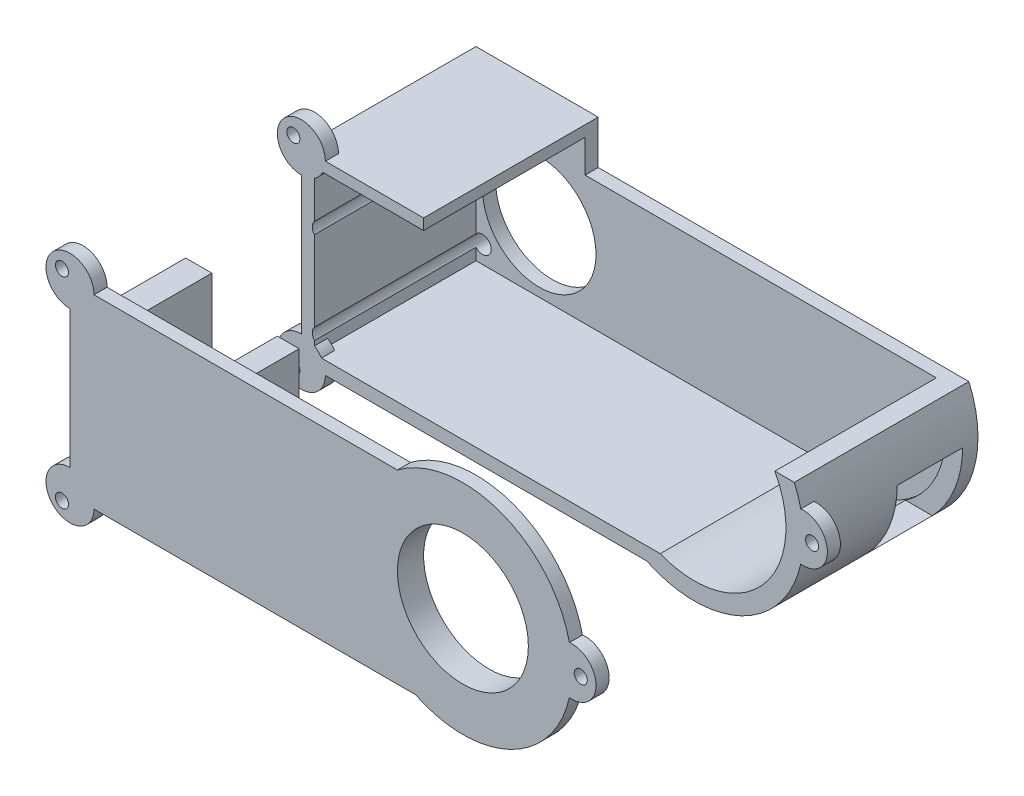
SolidWorks part; units mm, degrees
ref_plane "Front Plane" through (0, 0, 0) normal (0, 0, 1) x (1, 0, 0)
ref_plane "Top Plane" through (0, 0, 0) normal (0, 1, 0) x (1, 0, 0)
ref_plane "Right Plane" through (0, 0, 0) normal (1, 0, 0) x (0, 0, -1)
sketch "Sketch1" plane through (0, 0, 0) normal (0, 0, 1) x (1, 0, 0)
  line L1 (0, 0) -> (75, 0)
  line L2 (0, 0) -> (0, -42.5)
  line L3 (0, -42.5) -> (79.1028, -42.5)
  arc A0 (79.1028, -42.5) -> (75, 0) centre (90, -20) ccw
  dimension "D4" = 50
extrude "Boss-Extrude1" add sketch "Sketch1" along normal blind 40
sketch "Sketch2" plane through (0, 0, 40) normal (0, 0, 1) x (1, 0, 0)
  line L0 (0, 0) -> (0, -42.5) construction
  line L1 (3, -2.5) -> (78.3918, -2.5)
  line L2 (3, -2.5) -> (3, -39.5)
  line L3 (3, -39.5) -> (82.2058, -39.5)
  line L4 (75, 0) -> (0, 0) construction
  arc A0 (82.2058, -39.5) -> (78.3918, -2.5) centre (90, -20) ccw
  arc A1 (79.1028, -42.5) -> (75, 0) centre (90, -20) ccw construction
  dimension "D3" = 42
  dimension "D1" = 3
  dimension "D2" = 37
  dimension "D4" = 2.5
extrude "Cut-Extrude1" cut sketch "Sketch2" against normal blind 37
sketch "Sketch8" plane through (0, 0, 0) normal (0, 0, -1) x (-1, 0, 0)
  line L0 (-75, 0) -> (0, 0) construction
  line L1 (-66.3291, 0) -> (-28, 0)
  line L2 (-118, 0) -> (-118, -10)
  line L3 (-118, -10) -> (-28, -10)
  line L4 (-28, 0) -> (-28, -10)
  line L7 (-3, -2.5) -> (-3, -39.5) construction
  line L10 (-118, 0) -> (-118, 13.3555)
  line L11 (-118, 13.3555) -> (-66.3291, 13.3555)
  line L12 (-66.3291, 0) -> (-66.3291, 13.3555)
  dimension "D1" = 90
  dimension "D2" = 10
  dimension "D3" = 25
extrude "Cut-Extrude7" cut sketch "Sketch8" against normal up to next
sketch "Sketch4" plane through (0, 0, 3) normal (0, 0, 1) x (1, 0, 0)
  line L4 (3, -2.5) -> (3, -39.5) construction
  circle A0 centre (17.5, -24.5) radius 13
  dimension "D1" = 26
  dimension "D2" = 14.5
extrude "Cut-Extrude4" cut sketch "Sketch4" against normal blind 20
sketch "Sketch14" plane through (3, 0, 0) normal (1, 0, 0) x (0, 0, -1)
  line L1 (-3.5, -20.3065) -> (-18.5, -20.3065)
  line L2 (-3.5, -20.3065) -> (-3.5, -37.3065)
  line L3 (-3.5, -37.3065) -> (-18.5, -37.3065)
  line L4 (-18.5, -20.3065) -> (-18.5, -37.3065)
  line L5 (0, -45) -> (0, -10) construction
  dimension "D1" = 3.5
  dimension "D2" = 17
  dimension "D3" = 15
extrude "Cut-Extrude12" cut sketch "Sketch14" along normal through all
ref_plane "Plane11" through (0, -21.25, 0) normal (0, 1, 0) x (1, 0, 0)
sketch "Sketch9" plane through (0, 0, 40) normal (0, 0, 1) x (1, 0, 0)
  line L1 (0, -42.5) -> (79.1028, -42.5) construction
  circle A0 centre (3.5, -16.5) radius 1.5
  circle A1 centre (96.5, -11) radius 1.5
  circle A2 centre (96.5, -37.5) radius 1.5
  circle A3 centre (3.5, -37.5) radius 1.5
  circle A5 centre (17.5, -24.5) radius 13 construction
  dimension "D1" = 26.5
  dimension "D2" = 5
  dimension "D3" = 79
  dimension "D4" = 93
  dimension "D5" = 21
extrude "Cut-Extrude8" [suppressed] cut sketch "Sketch9" against normal blind 10
ref_plane "Plane12" through (0, 0, 90) normal (0, 0, 1) x (1, 0, 0)
sketch "Sketch15" plane through (0, 0, 90) normal (0, 0, 1) x (1, 0, 0)
  line L0 (0, -42.5) -> (79.1028, -42.5) construction
  line L1 (0, 0) -> (75, 0)
  line L2 (0, 0) -> (0, -42.5)
  line L3 (0, -42.5) -> (79.1028, -42.5)
  arc A0 (79.1028, -42.5) -> (75, 0) centre (90, -20) ccw
  arc A1 (79.1028, -42.5) -> (112.9129, -10) centre (90, -20) ccw construction
  dimension "D1" = 50
extrude "Boss-Extrude2" add sketch "Sketch15" along normal blind 3 separate body
sketch "Sketch17" plane through (0, 0, 93) normal (0, 0, 1) x (1, 0, 0)
  line L1 (3.5, -3) -> (78.3656, -3)
  line L2 (3.5, -3) -> (3.5, -39)
  line L3 (3.5, -39) -> (82.0401, -39)
  line L8 (75, 0) -> (0, 0) construction
  line L9 (0, -42.5) -> (79.1028, -42.5) construction
  line L11 (0, 0) -> (0, -42.5) construction
  arc A0 (82.0401, -39) -> (78.3656, -3) centre (90, -20) ccw
  arc A2 (79.1028, -42.5) -> (75, 0) centre (90, -20) ccw construction
  dimension "D3" = 41.2
  dimension "D1" = 3.5
  dimension "D2" = 3.5
  dimension "D4" = 3
extrude "Boss-Extrude3" add sketch "Sketch17" against normal blind 6
sketch "Sketch18" plane through (3.5, 0, 0) normal (-1, 0, 0) x (0, 0, 1)
  line L0 (87, -3) -> (87, -39) construction
  line L1 (87, -5.1981) -> (70, -5.1981)
  line L2 (87, -5.1981) -> (87, -34.585)
  line L3 (87, -34.585) -> (70, -34.585)
  line L4 (70, -5.1981) -> (70, -34.585)
  dimension "D1" = 17
extrude "Boss-Extrude4" add sketch "Sketch18" against normal blind 6
sketch "Sketch19" plane through (0, 0, 93) normal (0, 0, 1) x (1, 0, 0)
  circle A0 centre (90, -20) radius 15
  arc A1 (79.1028, -42.5) -> (75, 0) centre (90, -20) ccw construction
  dimension "D1" = 30
extrude "Cut-Extrude13" cut sketch "Sketch19" against normal up to surface (6 mm away) up to face at (27.962, -20.0593, 87)
sketch "Sketch20" plane through (0, 0, 93) normal (0, 0, 1) x (1, 0, 0)
  line L0 (0, -42.5) -> (79.1028, -42.5) construction
  circle A0 centre (0, 0) radius 5.5
  circle A1 centre (0, -42.5) radius 5.5
  circle A2 centre (115, -20) radius 5.5
  arc A3 (79.1028, -42.5) -> (75, 0) centre (90, -20) ccw construction
  circle A4 centre (-1.8367, 1.5) radius 1.5
  circle A5 centre (-1.8367, -44.5) radius 1.5
  circle A6 centre (117, -20) radius 1.5
  dimension "D1" = 11
  dimension "D2" = 11
  dimension "D3" = 11
  dimension "D4" = 3
  dimension "D5" = 3
  dimension "D6" = 3
  dimension "D7" = 2
  dimension "D8" = 46
  dimension "D9" = 2
extrude "Boss-Extrude5" add sketch "Sketch20" against normal up to surface (3 mm away) up to face at (49.4241, -20.2271, 90)
sketch "Sketch21" plane through (0, 0, 40) normal (0, 0, 1) x (1, 0, 0)
  circle A0 centre (0, 0) radius 5.5
  circle A1 centre (0, -42.5) radius 5.5
  arc A2 (0, -37) -> (5.5, -42.5) centre (0, -42.5) ccw construction
  circle A3 centre (115, -20) radius 5.5
  arc A4 (114.395, -25.4666) -> (114.395, -14.5334) centre (115, -20) ccw construction
  circle A5 centre (-1.8367, 1.5) radius 1.5
  circle A6 centre (-1.8367, -44.5) radius 1.5
  circle A7 centre (117, -20) radius 1.5
extrude "Boss-Extrude6" add sketch "Sketch21" against normal blind 3
sketch "Sketch22" plane through (0, 0, 3) normal (0, 0, 1) x (1, 0, 0)
  circle A0 centre (90, -20) radius 21
  arc A1 (82.2058, -39.5) -> (108.4662, -10) centre (90, -20) ccw construction
extrude "Cut-Extrude14" cut sketch "Sketch22" along normal blind 66
sketch "Sketch23" plane through (0, 0, 0) normal (0, 0, -1) x (-1, 0, 0)
  circle A0 centre (-4.5, -35.5) radius 2
  circle A1 centre (-4.5, -14.5) radius 2
  circle A2 centre (-17.5, -24.5) radius 13 construction
  dimension "D2" = 4
  dimension "D3" = 4
  dimension "D1" = 13
  dimension "D4" = 10
  dimension "D5" = 11
extrude "Cut-Extrude15" cut sketch "Sketch23" against normal up to surface (40 mm away) up to face at (43.8507, -20.7343, 40)
sketch "Sketch24" plane through (9.5, 0, 0) normal (1, 0, 0) x (0, 0, -1)
  line L0 (-87, -5.1981) -> (-70, -5.1981) construction
  line L1 (-75, -5.1981) -> (-87, -5.1981)
  line L2 (-75, -5.1981) -> (-75, -34.585)
  line L3 (-75, -34.585) -> (-87, -34.585)
  line L4 (-87, -5.1981) -> (-87, -34.585)
  line L5 (-87, -34.585) -> (-87, -5.1981) construction
  line L6 (-70, -34.585) -> (-87, -34.585) construction
  dimension "D1" = 12
extrude "Boss-Extrude7" add sketch "Sketch24" along normal blind 5 from offset 20
equation "\"D2@Sketch20\"=\"D1@Sketch20\""
equation "\"D3@Sketch20\"=\"D1@Sketch20\""
equation "\"D5@Sketch20\"=\"D4@Sketch20\""
equation "\"D6@Sketch20\"=\"D4@Sketch20\""
equation "\"D3@Sketch23\"=\"D2@Sketch23\""
